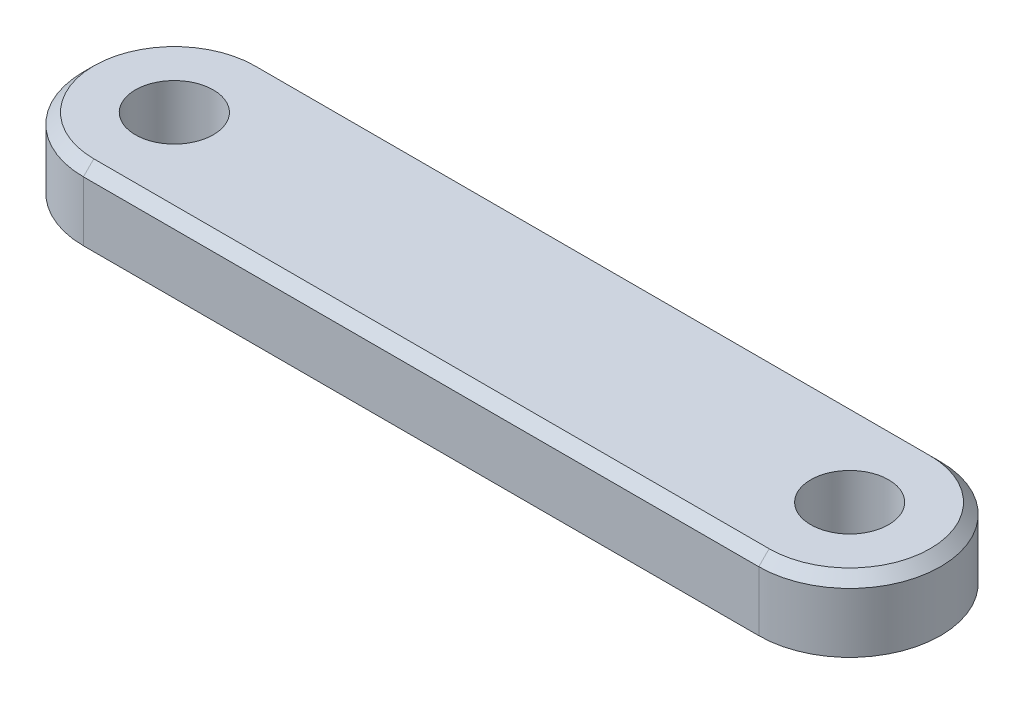
SolidWorks part; units mm, degrees
ref_plane "Front Plane" through (0, 0, 0) normal (0, 0, 1) x (1, 0, 0)
ref_plane "Top Plane" through (0, 0, 0) normal (0, 1, 0) x (1, 0, 0)
ref_plane "Right Plane" through (0, 0, 0) normal (1, 0, 0) x (0, 0, -1)
sketch "Sketch1" plane through (0, 0, 0) normal (0, 1, 0) x (1, 0, 0)
  line L0 (-18.0944, 0) -> (24.4801, 0) construction
  line L1 (-13, 0) -> (13, 0) construction
  line L2 (-13, 3.5) -> (13, 3.5)
  line L3 (-13, -3.5) -> (13, -3.5)
  line L4 (0, 10.1131) -> (0, -14.786) construction
  arc A0 (-13, 3.5) -> (-13, -3.5) centre (-13, 0) ccw
  arc A1 (13, -3.5) -> (13, 3.5) centre (13, 0) ccw
  circle A2 centre (-13, 0) radius 1.5
  circle A4 centre (13, 0) radius 1.5
  point P5 (0, 0)
  point P11 (-16.5, 0)
  point P12 (16.5, 0)
  dimension "D3" = 3
  dimension "D1" = 7
  dimension "D2" = 33
extrude "Boss-Extrude1" add sketch "Sketch1" along normal mid plane 2.7
chamfer "Chamfer1" distance 0.4 angle 45 4 edges at (16.5, 1.35, 0) (0, 1.35, -3.5) (-16.5, 1.35, 0) (0, 1.35, 3.5)
